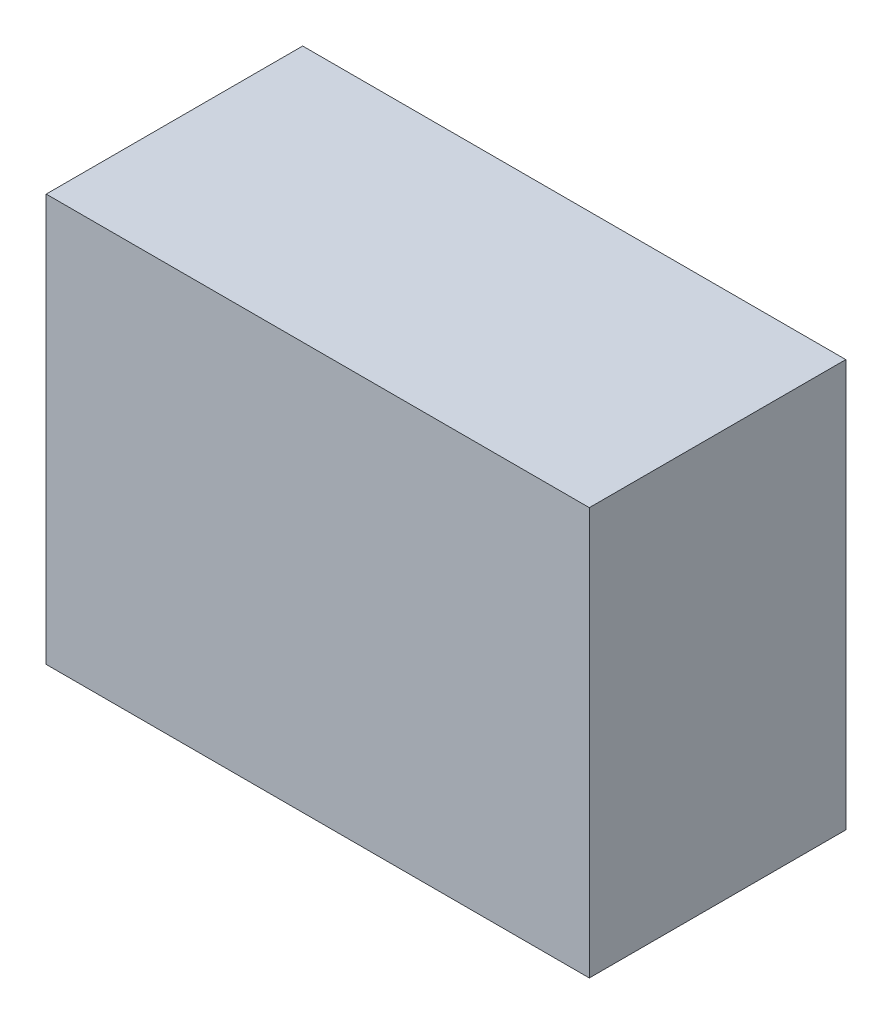
SolidWorks part; units mm, degrees
ref_plane "前视基准面" through (0, 0, 0) normal (0, 0, 1) x (1, 0, 0)
ref_plane "上视基准面" through (0, 0, 0) normal (0, 1, 0) x (1, 0, 0)
ref_plane "右视基准面" through (0, 0, 0) normal (1, 0, 0) x (0, 0, -1)
other "Configuration Table"
sketch "草图1" plane through (0, 0, 0) normal (0, 1, 0) x (1, 0, 0)
  line L1 (36, -17) -> (-36, -17)
  line L2 (36, -17) -> (36, 17)
  line L3 (36, 17) -> (-36, 17)
  line L4 (-36, -17) -> (-36, 17)
  line L5 (36, -17) -> (-36, 17) construction
  line L6 (36, 17) -> (-36, -17) construction
  point P0 (0, 0)
extrude "凸台-拉伸1" add sketch "草图1" along normal blind 54
